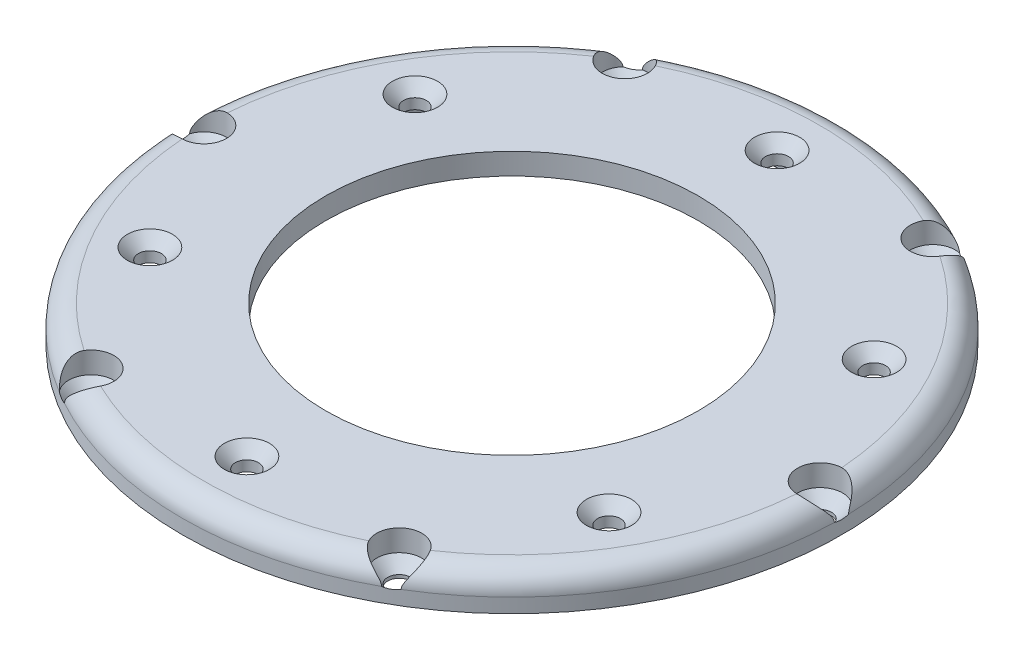
SolidWorks part; units mm, degrees
ref_plane "Front Plane" through (0, 0, 0) normal (0, 0, 1) x (1, 0, 0)
ref_plane "Top Plane" through (0, 0, 0) normal (0, 1, 0) x (1, 0, 0)
ref_plane "Right Plane" through (0, 0, 0) normal (1, 0, 0) x (0, 0, -1)
sketch "Sketch1" plane through (0, 0, 0) normal (0, 0, 1) x (1, 0, 0)
  line L0 (0, 96.254) -> (0, -102.214) construction
  line L1 (40, 1) -> (40, 0)
  line L2 (40, 0) -> (46, 0)
  line L3 (46, 0) -> (46, 2)
  line L5 (43, 5) -> (26, 5)
  line L6 (26, 5) -> (26, 2)
  line L7 (26, 2) -> (39, 2)
  arc A0 (46, 2) -> (43, 5) centre (43, 2) ccw
  arc A1 (39, 2) -> (40, 1) centre (39, 1) cw
  point P1 (37, 5)
  point P17 (43, 0)
  dimension "D4" = 3
  dimension "D5" = 1
  dimension "D1" = 80
  dimension "D2" = 5
  dimension "D3" = 3
  dimension "D6" = 52
  dimension "D7" = 6
  dimension "D8" = 74
revolve "Revolve1" add sketch "Sketch1" angle 360 about L0
hole_wizard "CSK for M3 Countersunk Flat Head Screw1" positions "Sketch2" profile "Sketch3" countersink size "M3" standard "ISO" end condition through all
sketch "Sketch2" plane through (0, 5, 0) normal (0, 1, 0) x (1, 0, 0)
  point P6 (43, 0)
sketch "Sketch3" plane through (43, 5, 0) normal (1, 0, 0) x (0, 0, 1)
  line L0 (0, 0) -> (0, 5)
  line L1 (0, 5) -> (1.6, 5)
  line L2 (1.6, 5) -> (1.6, 4.55)
  line L3 (1.6, 4.55) -> (3.15, 3)
  line L4 (3.15, 3) -> (3.15, 0)
  line L6 (3.15, 0) -> (0, 0)
  line L7 (-1.6, 4.55) -> (-3.15, 3) construction
  line L11 (0, -6.35) -> (0, 107.95) construction
  dimension "Thru Hole Dia." = 3.2
  dimension "Thru Hole Depth" = 5
  dimension "C'Sink Dia." = 6.3
  dimension "C'Sink Angle" = 90
  dimension "Head Clearance" = 3
pattern_circular "CirPattern1" count 6 over 360 about axis through (0, 0, 0) along (0, 1, 0) of "CSK for M3 Countersunk Flat Head Screw1"
hole_wizard "CSK for M3 Countersunk Flat Head Screw2" positions "Sketch4" profile "Sketch5" countersink size "M3" standard "ISO" end condition through all
sketch "Sketch4" plane through (0, 5, 0) normal (0, 1, 0) x (1, 0, 0)
  circle A0 centre (0, 0) radius 37
  point P0 (0, 37)
sketch "Sketch5" plane through (0, 5, -37) normal (1, 0, 0) x (0, 0, 1)
  line L0 (0, 0) -> (0, 5)
  line L1 (0, 5) -> (1.6, 5)
  line L2 (1.6, 5) -> (1.6, 1.55)
  line L3 (1.6, 1.55) -> (3.15, 0)
  line L5 (3.15, 0) -> (0, 0)
  line L6 (-1.6, 1.55) -> (-3.15, 0) construction
  line L11 (0, -6.35) -> (0, 107.95) construction
  dimension "Thru Hole Dia." = 3.2
  dimension "Thru Hole Depth" = 5
  dimension "Near C'Sink Dia." = 6.3
  dimension "Near C'Sink Angle" = 90
pattern_circular "CirPattern2" count 6 over 360 about axis through (0, 0, 0) along (0, 1, 0) of "CSK for M3 Countersunk Flat Head Screw2"
